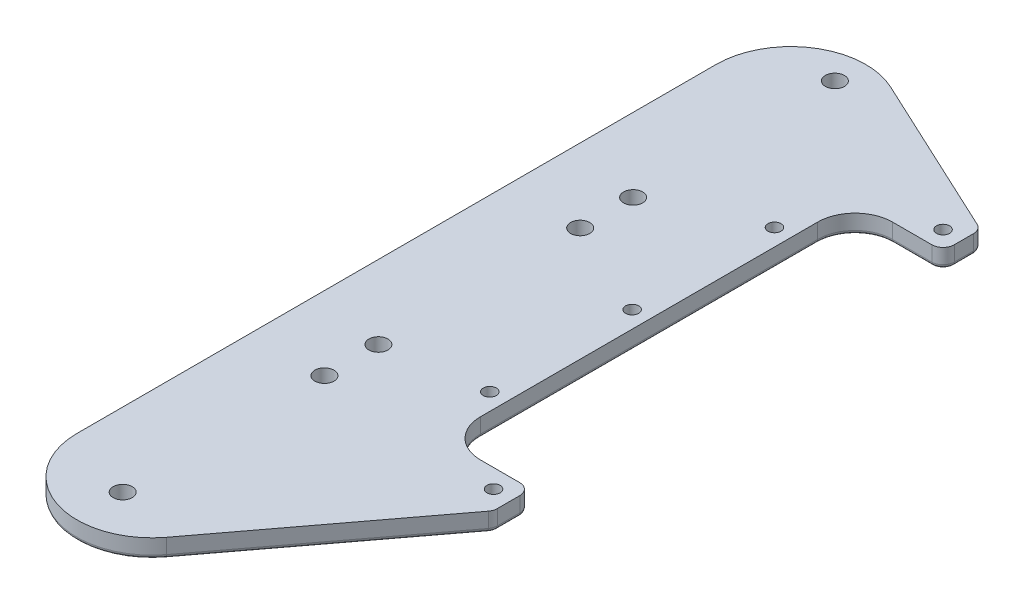
SolidWorks part; units mm, degrees
ref_plane "Front Plane" through (0, 0, 0) normal (0, 0, 1) x (1, 0, 0)
ref_plane "Top Plane" through (0, 0, 0) normal (0, 1, 0) x (1, 0, 0)
ref_plane "Right Plane" through (0, 0, 0) normal (1, 0, 0) x (0, 0, -1)
sketch "Sketch1" plane through (0, 0, 0) normal (0, 1, 0) x (1, 0, 0)
  line L0 (28.48, -65) -> (28.48, -55)
  line L1 (28.48, -55) -> (5, -55)
  line L2 (5, -55) -> (5, 55)
  line L3 (5, 55) -> (28.48, 55)
  line L4 (28.48, 55) -> (28.48, 65)
  line L5 (28.48, 65) -> (-45, 99.2643)
  line L6 (-45, 99.2643) -> (-45, -162.5113)
  line L7 (-45, -162.5113) -> (28.48, -65)
  line L8 (0, 0) -> (5, 0) construction
  line L9 (23.48, -60) -> (23.48, -55) construction
  line L10 (23.48, 60) -> (28.48, 60) construction
  circle A0 centre (0.48, 0) radius 1.75
  circle A2 centre (0.48, -38) radius 1.75
  circle A3 centre (0.48, -38) radius 1.75 construction
  circle A4 centre (23.48, -60) radius 1.75
  circle A5 centre (23.48, -60) radius 1.75 construction
  circle A6 centre (0.48, 38) radius 1.75
  circle A7 centre (0.48, 38) radius 1.75 construction
  circle A8 centre (23.48, 60) radius 1.75
  circle A9 centre (23.48, 60) radius 1.75 construction
  circle A10 centre (23.48, 60) radius 1.75 construction
  circle A11 centre (0.48, 0) radius 1.75 construction
  point P30 (5, 0)
  point P33 (28.48, 60)
  dimension "D1" = 115
  dimension "D2" = 5
  dimension "D3" = 143
  dimension "D4" = 50
extrude "Boss-Extrude1" add sketch "Sketch1" along normal blind 5
fillet "Fillet3" radius 10 2 edges at (5, 2.5, 55) (5, 2.5, -55)
fillet "Fillet4" radius 3 4 edges at (28.48, 2.5, -65) (28.48, 2.5, 65) (28.48, 2.5, 55) (28.48, 2.5, -55)
fillet "Fillet5" radius 20 2 edges at (-45, 2.5, 162.5113) (-45, 2.5, -99.2643)
sketch "Sketch2" plane through (0, 0, 0) normal (0, -1, 0) x (1, 0, 0)
  circle A0 centre (-25.3273, 41.9336) radius 4
  circle A1 centre (-25.3273, -11.9336) radius 4
  circle A2 centre (-25.3273, -26.0664) radius 4
  circle A3 centre (-25.3273, -79.9336) radius 4
  circle A8 centre (-25.3273, 56.3434) radius 4
  circle A9 centre (-25.3273, 110.2107) radius 4
  circle A12 centre (-25.3273, -79.9336) radius 3.29 construction
  circle A13 centre (-25.3273, -26.0664) radius 3.29 construction
  circle A14 centre (-25.3273, -11.9336) radius 3.29 construction
  circle A15 centre (-25.3273, 41.9336) radius 3.29 construction
  circle A16 centre (-25.3273, 56.3434) radius 3.29 construction
  circle A17 centre (-25.3273, 110.2107) radius 3.29 construction
  dimension "D1" = 8
extrude "Boss-Extrude2" add sketch "Sketch2" along normal up to surface (5 mm away)
sketch "Sketch3" plane through (0, 5, 0) normal (0, 1, 0) x (1, 0, 0)
  circle A0 centre (-25.3273, 79.9336) radius 2.55
  circle A1 centre (-25.3273, 26.0664) radius 2.55
  circle A2 centre (-25.3273, 11.9336) radius 2.55
  circle A3 centre (-25.3273, -41.9336) radius 2.55
  circle A4 centre (-25.3273, 79.9336) radius 4 construction
  circle A5 centre (-25.3273, 26.0664) radius 4 construction
  circle A6 centre (-25.3273, -41.9336) radius 4 construction
  circle A7 centre (-25.3273, 11.9336) radius 4 construction
  circle A8 centre (-25.3273, -56.3434) radius 2.55
  circle A9 centre (-25.3273, -110.2107) radius 2.55
  circle A10 centre (-25.3273, -110.2107) radius 4 construction
  circle A11 centre (-25.3273, -56.3434) radius 4 construction
  dimension "D1" = 5.1
extrude "Cut-Extrude1" cut sketch "Sketch3" against normal offset from surface (7 mm away) 3 up to face at (-25.3273, -5, -75.9336)
sketch "Sketch4" plane through (0, -5, 0) normal (0, -1, 0) x (1, 0, 0)
  circle A0 centre (-25.3273, -79.9336) radius 1.55
  circle A1 centre (-25.3273, -26.0664) radius 1.55
  circle A2 centre (-25.3273, -11.9336) radius 1.55
  circle A3 centre (-25.3273, 41.9336) radius 1.55
  circle A4 centre (-25.3273, 41.9336) radius 4 construction
  circle A5 centre (-25.3273, -11.9336) radius 4 construction
  circle A6 centre (-25.3273, -26.0664) radius 4 construction
  circle A7 centre (-25.3273, -79.9336) radius 4 construction
  circle A8 centre (-25.3273, 56.3434) radius 1.55
  circle A9 centre (-25.3273, 110.2107) radius 1.55
  circle A10 centre (-25.3273, 110.2107) radius 4 construction
  circle A11 centre (-25.3273, 56.3434) radius 4 construction
  dimension "D1" = 3.1
extrude "Cut-Extrude2" cut sketch "Sketch4" against normal through all both and the other way through all
fillet "Fillet6" radius 2 12 edges at (-25.3273, 0, -75.9336) (-25.3273, 0, -22.0664) (-25.3273, 0, -7.9336) (-25.3273, 0, 45.9336) (-25.3273, -5, 45.9336) (-25.3273, -5, -7.9336) (-25.3273, -5, -22.0664) (-25.3273, -5, -75.9336) (-25.3273, 0, 114.2107) (-25.3273, -5, 114.2107) (-25.3273, 0, 60.3434) (-25.3273, -5, 60.3434)
fillet "Fillet7" radius 1 16 edges at (20.24, 0, -55) (27.6013, 0, -55.8787) (28.48, 0, -60.5444) (28.0102, 0, -64.7007) (5.1001, 0, -75.9022) (-35.746, 0, -84.7384) (-45, 0, 17.4335) (-31.3461, 0, 121.704) (9.4243, 0, 90.2878) (28.325, 0, 64.9481) (28.48, 0, 60.9981) (27.6013, 0, 55.8787) (20.24, 0, 55) (7.9289, 0, 52.0711) (5, 0, 0) (7.9289, 0, -52.0711)
sketch "Sketch6" plane through (0, 0, 0) normal (0, -1, 0) x (-1, 0, 0)
  line L0 (40, 56) -> (-15, 56) construction
  line L1 (44, -102.7376) -> (44, 67.8706) construction
  arc A0 (-4, 45) -> (-15, 56) centre (-15, 45) ccw construction
  text T0 "^UP\r\nDC-DC Mount V2\r\nhitchco-mk4"
  dimension "D1" = 55
extrude "Cut-Extrude3" cut sketch "Sketch6" against normal blind 1
